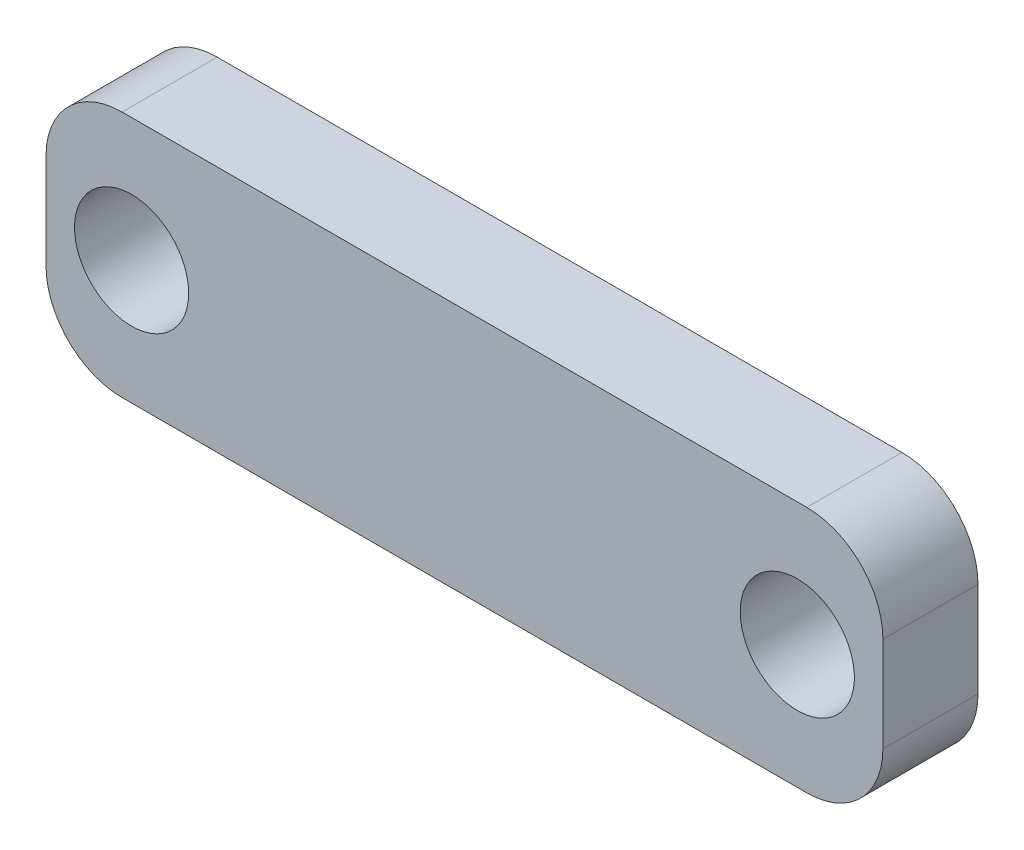
SolidWorks part; units mm, degrees
ref_plane "Front Plane" through (0, 0, 0) normal (0, 0, 1) x (1, 0, 0)
ref_plane "Top Plane" through (0, 0, 0) normal (0, 1, 0) x (1, 0, 0)
ref_plane "Right Plane" through (0, 0, 0) normal (1, 0, 0) x (0, 0, -1)
sketch "Sketch1" plane through (0, 0, 0) normal (0, 0, 1) x (1, 0, 0)
  line L0 (0, 0) -> (0, 6.6368) construction
  line L1 (-11.6604, 0) -> (11.6321, 0) construction
  line L2 (-11, -3.25) -> (11, -3.25)
  line L3 (-11, -3.25) -> (-11, 3.25)
  line L4 (-11, 3.25) -> (11, 3.25)
  line L5 (11, -3.25) -> (11, 3.25)
  line L6 (-11, -3.25) -> (11, 3.25) construction
  line L7 (-11, 3.25) -> (11, -3.25) construction
  circle A0 centre (-8.75, 0) radius 1.5
  circle A1 centre (8.75, 0) radius 1.5
  dimension "D3" = 17.5
  dimension "D4" = 3
  dimension "D1" = 22
  dimension "D2" = 6.5
extrude "Boss-Extrude1" add sketch "Sketch1" along normal blind 2.5
fillet "Fillet4" radius 2 4 edges at (-11, 3.25, 1.25) (-11, -3.25, 1.25) (11, -3.25, 1.25) (11, 3.25, 1.25)
